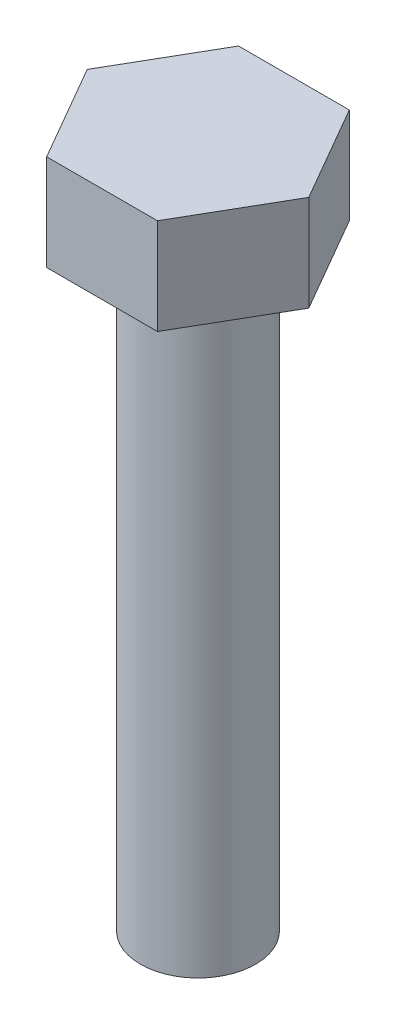
SolidWorks part; units mm, degrees
ref_plane "Front Plane" through (0, 0, 0) normal (0, 0, 1) x (1, 0, 0)
ref_plane "Top Plane" through (0, 0, 0) normal (0, 1, 0) x (1, 0, 0)
ref_plane "Right Plane" through (0, 0, 0) normal (1, 0, 0) x (0, 0, -1)
sketch "Sketch1" plane through (0, 0, 0) normal (0, 1, 0) x (1, 0, 0)
  circle A0 centre (0, 0) radius 6
  dimension "D1" = 12
extrude "Boss-Extrude1" add sketch "Sketch1" along normal blind 62
sketch "Sketch2" plane through (0, 62, 0) normal (0, 1, 0) x (1, 0, 0)
  line L1 (11.547, 0) -> (5.7735, 10)
  line L2 (5.7735, 10) -> (-5.7735, 10)
  line L3 (-5.7735, 10) -> (-11.547, 0)
  line L4 (-11.547, 0) -> (-5.7735, -10)
  line L5 (-5.7735, -10) -> (5.7735, -10)
  line L6 (5.7735, -10) -> (11.547, 0)
  circle A0 centre (0, 0) radius 10 construction
  dimension "D1" = 20
extrude "Boss-Extrude2" add sketch "Sketch2" along normal blind 10
